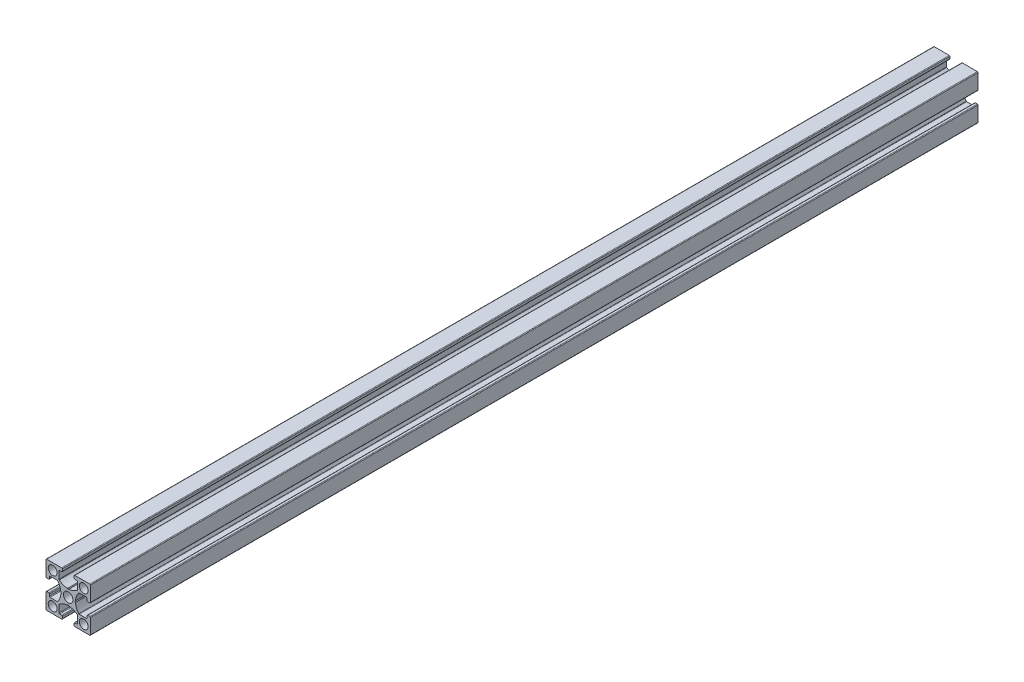
SolidWorks part; units mm, degrees
ref_plane "정면" through (0, 0, 0) normal (0, 0, 1) x (1, 0, 0)
ref_plane "윗면" through (0, 0, 0) normal (0, 1, 0) x (1, 0, 0)
ref_plane "우측면" through (0, 0, 0) normal (1, 0, 0) x (0, 0, -1)
sketch "Model" plane through (0, 0, 0) normal (0, 0, 1) x (1, 0, 0)
  line L0 (2292.4151, 1187.1915) -> (2314.8128, 1187.1915) construction
  line L1 (2307.7639, 1192.1343) -> (2307.7639, 1195.3915)
  line L2 (2307.4639, 1195.6915) -> (2306.5639, 1195.6915)
  line L3 (2306.2639, 1195.9915) -> (2306.2639, 1196.8915)
  line L4 (2306.5639, 1197.1915) -> (2313.3139, 1197.1915)
  line L5 (2313.6139, 1196.8915) -> (2313.6139, 1190.1415)
  line L6 (2313.3139, 1189.8415) -> (2312.4139, 1189.8415)
  line L7 (2312.1139, 1190.1415) -> (2312.1139, 1191.0415)
  line L8 (2311.8139, 1191.3415) -> (2308.5567, 1191.3415)
  line L9 (2306.9212, 1187.4988) -> (2306.6139, 1187.1915)
  line L10 (2306.6139, 1187.1915) -> (2306.9212, 1186.8843)
  line L11 (2308.5567, 1183.0415) -> (2311.8139, 1183.0415)
  line L12 (2312.1139, 1183.3415) -> (2312.1139, 1184.2415)
  line L13 (2312.4139, 1184.5415) -> (2313.3139, 1184.5415)
  line L14 (2313.6139, 1184.2415) -> (2313.6139, 1177.4915)
  line L15 (2313.3139, 1177.1915) -> (2306.5639, 1177.1915)
  line L16 (2306.2639, 1177.4915) -> (2306.2639, 1178.3915)
  line L17 (2306.5639, 1178.6915) -> (2307.4639, 1178.6915)
  line L18 (2307.7639, 1178.9915) -> (2307.7639, 1182.2488)
  line L19 (2303.9212, 1183.8843) -> (2303.6139, 1184.1915)
  line L20 (2303.6139, 1184.1915) -> (2303.3066, 1183.8843)
  line L21 (2299.4639, 1182.2488) -> (2299.4639, 1178.9915)
  line L22 (2299.7639, 1178.6915) -> (2300.6639, 1178.6915)
  line L23 (2300.9639, 1178.3915) -> (2300.9639, 1177.4915)
  line L24 (2300.6639, 1177.1915) -> (2293.9139, 1177.1915)
  line L25 (2293.6139, 1177.4915) -> (2293.6139, 1184.2415)
  line L26 (2293.9139, 1184.5415) -> (2294.8139, 1184.5415)
  line L27 (2295.1139, 1184.2415) -> (2295.1139, 1183.3415)
  line L28 (2295.4139, 1183.0415) -> (2298.6712, 1183.0415)
  line L29 (2300.3066, 1186.8843) -> (2300.6139, 1187.1915)
  line L30 (2300.6139, 1187.1915) -> (2300.3066, 1187.4988)
  line L31 (2298.6712, 1191.3415) -> (2295.4139, 1191.3415)
  line L32 (2295.1139, 1191.0415) -> (2295.1139, 1190.1415)
  line L33 (2294.8139, 1189.8415) -> (2293.9139, 1189.8415)
  line L34 (2293.6139, 1190.1415) -> (2293.6139, 1196.8915)
  line L35 (2293.9139, 1197.1915) -> (2300.6639, 1197.1915)
  line L36 (2300.9639, 1196.8915) -> (2300.9639, 1195.9915)
  line L37 (2300.6639, 1195.6915) -> (2299.7639, 1195.6915)
  line L38 (2299.4639, 1195.3915) -> (2299.4639, 1192.1343)
  line L39 (2303.3066, 1190.4988) -> (2303.6139, 1190.1915)
  line L40 (2303.6139, 1190.1915) -> (2303.9212, 1190.4988)
  line L41 (2294.1139, 1194.1915) -> (2299.1139, 1194.1915) construction
  line L42 (2296.6139, 1196.6915) -> (2296.6139, 1191.6915) construction
  line L43 (2294.1139, 1180.1915) -> (2299.1139, 1180.1915) construction
  line L44 (2296.6139, 1177.6915) -> (2296.6139, 1182.6915) construction
  line L45 (2303.6139, 1198.3904) -> (2303.6139, 1175.9927) construction
  line L46 (2313.1139, 1194.1915) -> (2308.1139, 1194.1915) construction
  line L47 (2310.6139, 1196.6915) -> (2310.6139, 1191.6915) construction
  line L48 (2310.6139, 1177.6915) -> (2310.6139, 1182.6915) construction
  line L49 (2313.1139, 1180.1915) -> (2308.1139, 1180.1915) construction
  circle A0 centre (2303.6139, 1187.1915) radius 2.15
  circle A1 centre (2296.6139, 1194.1915) radius 2
  circle A2 centre (2296.6139, 1180.1915) radius 2
  circle A3 centre (2310.6139, 1194.1915) radius 2
  circle A4 centre (2310.6139, 1180.1915) radius 2
  arc A5 (2307.7639, 1195.3915) -> (2307.4639, 1195.6915) centre (2307.4639, 1195.3915) ccw
  arc A6 (2306.2639, 1195.9915) -> (2306.5639, 1195.6915) centre (2306.5639, 1195.9915) ccw
  arc A7 (2306.5639, 1197.1915) -> (2306.2639, 1196.8915) centre (2306.5639, 1196.8915) ccw
  arc A8 (2313.6139, 1196.8915) -> (2313.3139, 1197.1915) centre (2313.3139, 1196.8915) ccw
  arc A9 (2313.3139, 1189.8415) -> (2313.6139, 1190.1415) centre (2313.3139, 1190.1415) ccw
  arc A10 (2312.1139, 1190.1415) -> (2312.4139, 1189.8415) centre (2312.4139, 1190.1415) ccw
  arc A11 (2312.1139, 1191.0415) -> (2311.8139, 1191.3415) centre (2311.8139, 1191.0415) ccw
  arc A12 (2308.5567, 1191.3415) -> (2308.3217, 1191.2281) centre (2308.5567, 1191.0415) ccw
  arc A13 (2308.3217, 1191.2281) -> (2306.9212, 1187.4988) centre (2313.4048, 1187.1915) ccw
  arc A14 (2306.9212, 1186.8843) -> (2308.3217, 1183.155) centre (2313.4048, 1187.1915) ccw
  arc A15 (2308.3217, 1183.155) -> (2308.5567, 1183.0415) centre (2308.5567, 1183.3415) ccw
  arc A16 (2311.8139, 1183.0415) -> (2312.1139, 1183.3415) centre (2311.8139, 1183.3415) ccw
  arc A17 (2312.4139, 1184.5415) -> (2312.1139, 1184.2415) centre (2312.4139, 1184.2415) ccw
  arc A18 (2313.6139, 1184.2415) -> (2313.3139, 1184.5415) centre (2313.3139, 1184.2415) ccw
  arc A19 (2313.3139, 1177.1915) -> (2313.6139, 1177.4915) centre (2313.3139, 1177.4915) ccw
  arc A20 (2306.2639, 1177.4915) -> (2306.5639, 1177.1915) centre (2306.5639, 1177.4915) ccw
  arc A21 (2306.5639, 1178.6915) -> (2306.2639, 1178.3915) centre (2306.5639, 1178.3915) ccw
  arc A22 (2307.4639, 1178.6915) -> (2307.7639, 1178.9915) centre (2307.4639, 1178.9915) ccw
  arc A23 (2307.7639, 1182.2488) -> (2307.6505, 1182.4837) centre (2307.4639, 1182.2488) ccw
  arc A24 (2307.6505, 1182.4837) -> (2303.9212, 1183.8843) centre (2303.6139, 1177.4007) ccw
  arc A25 (2303.3066, 1183.8843) -> (2299.5774, 1182.4837) centre (2303.6139, 1177.4007) ccw
  arc A26 (2299.5774, 1182.4837) -> (2299.4639, 1182.2488) centre (2299.7639, 1182.2488) ccw
  arc A27 (2299.4639, 1178.9915) -> (2299.7639, 1178.6915) centre (2299.7639, 1178.9915) ccw
  arc A28 (2300.9639, 1178.3915) -> (2300.6639, 1178.6915) centre (2300.6639, 1178.3915) ccw
  arc A29 (2300.6639, 1177.1915) -> (2300.9639, 1177.4915) centre (2300.6639, 1177.4915) ccw
  arc A30 (2293.6139, 1177.4915) -> (2293.9139, 1177.1915) centre (2293.9139, 1177.4915) ccw
  arc A31 (2293.9139, 1184.5415) -> (2293.6139, 1184.2415) centre (2293.9139, 1184.2415) ccw
  arc A32 (2295.1139, 1184.2415) -> (2294.8139, 1184.5415) centre (2294.8139, 1184.2415) ccw
  arc A33 (2295.1139, 1183.3415) -> (2295.4139, 1183.0415) centre (2295.4139, 1183.3415) ccw
  arc A34 (2298.6712, 1183.0415) -> (2298.9061, 1183.155) centre (2298.6712, 1183.3415) ccw
  arc A35 (2298.9061, 1183.155) -> (2300.3066, 1186.8843) centre (2293.8231, 1187.1915) ccw
  arc A36 (2300.3066, 1187.4988) -> (2298.9061, 1191.2281) centre (2293.8231, 1187.1915) ccw
  arc A37 (2298.9061, 1191.2281) -> (2298.6712, 1191.3415) centre (2298.6712, 1191.0415) ccw
  arc A38 (2295.4139, 1191.3415) -> (2295.1139, 1191.0415) centre (2295.4139, 1191.0415) ccw
  arc A39 (2294.8139, 1189.8415) -> (2295.1139, 1190.1415) centre (2294.8139, 1190.1415) ccw
  arc A40 (2293.6139, 1190.1415) -> (2293.9139, 1189.8415) centre (2293.9139, 1190.1415) ccw
  arc A41 (2293.9139, 1197.1915) -> (2293.6139, 1196.8915) centre (2293.9139, 1196.8915) ccw
  arc A42 (2300.9639, 1196.8915) -> (2300.6639, 1197.1915) centre (2300.6639, 1196.8915) ccw
  arc A43 (2300.6639, 1195.6915) -> (2300.9639, 1195.9915) centre (2300.6639, 1195.9915) ccw
  arc A44 (2299.7639, 1195.6915) -> (2299.4639, 1195.3915) centre (2299.7639, 1195.3915) ccw
  arc A45 (2299.4639, 1192.1343) -> (2299.5774, 1191.8994) centre (2299.7639, 1192.1343) ccw
  arc A46 (2299.5774, 1191.8994) -> (2303.3066, 1190.4988) centre (2303.6139, 1196.9824) ccw
  arc A47 (2303.9212, 1190.4988) -> (2307.6505, 1191.8994) centre (2303.6139, 1196.9824) ccw
  arc A48 (2307.6505, 1191.8994) -> (2307.7639, 1192.1343) centre (2307.4639, 1192.1343) ccw
extrude "보스-돌출1" add sketch "Model" along normal blind 400
